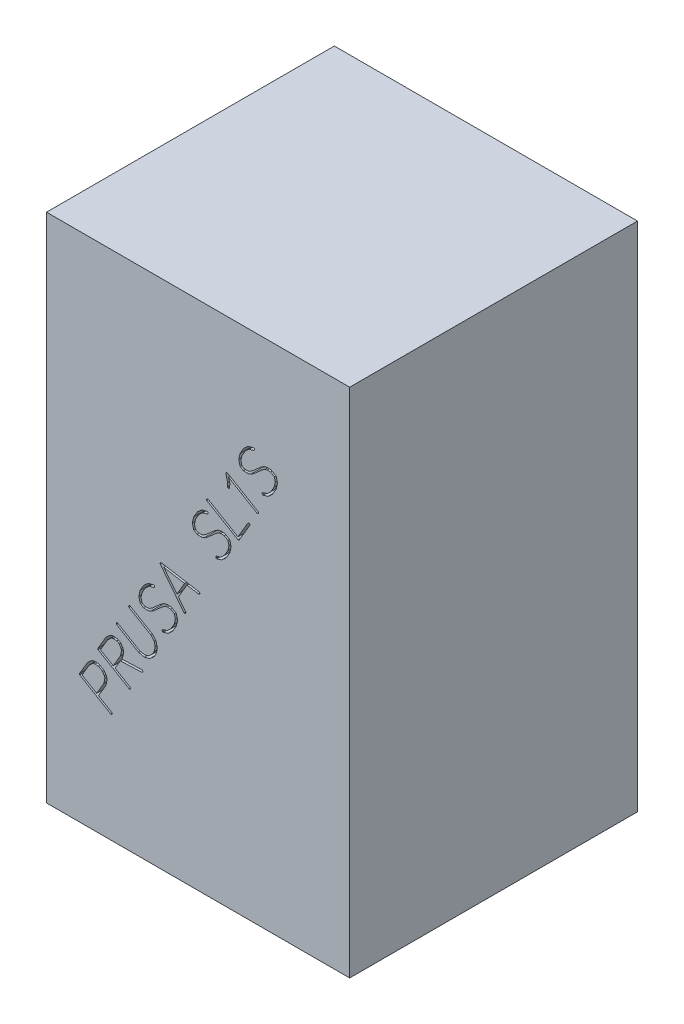
SolidWorks part; units mm, degrees
ref_plane "Front Plane" through (0, 0, 0) normal (0, 0, 1) x (1, 0, 0)
ref_plane "Top Plane" through (0, 0, 0) normal (0, 1, 0) x (1, 0, 0)
ref_plane "Right Plane" through (0, 0, 0) normal (1, 0, 0) x (0, 0, -1)
sketch "Sketch1" plane through (0, 0, 0) normal (0, 1, 0) x (1, 0, 0)
  line L1 (-118.5, -112.5) -> (118.5, -112.5)
  line L2 (-118.5, -112.5) -> (-118.5, 112.5)
  line L3 (-118.5, 112.5) -> (118.5, 112.5)
  line L4 (118.5, -112.5) -> (118.5, 112.5)
  line L5 (-118.5, -112.5) -> (118.5, 112.5) construction
  line L6 (-118.5, 112.5) -> (118.5, -112.5) construction
  point P0 (0, 0)
  dimension "D1" = 225
  dimension "D2" = 237
extrude "Boss-Extrude1" add sketch "Sketch1" along normal blind 400
sketch "Sketch2" plane through (0, 0, 112.5) normal (0, 0, 1) x (1, 0, 0)
  line L0 (118.5, 400) -> (-118.5, 0) construction
  text T0 "PRUSA SL1S" font "SWSimp" height 30
extrude "Cut-Extrude1" cut sketch "Sketch2" against normal blind 10
